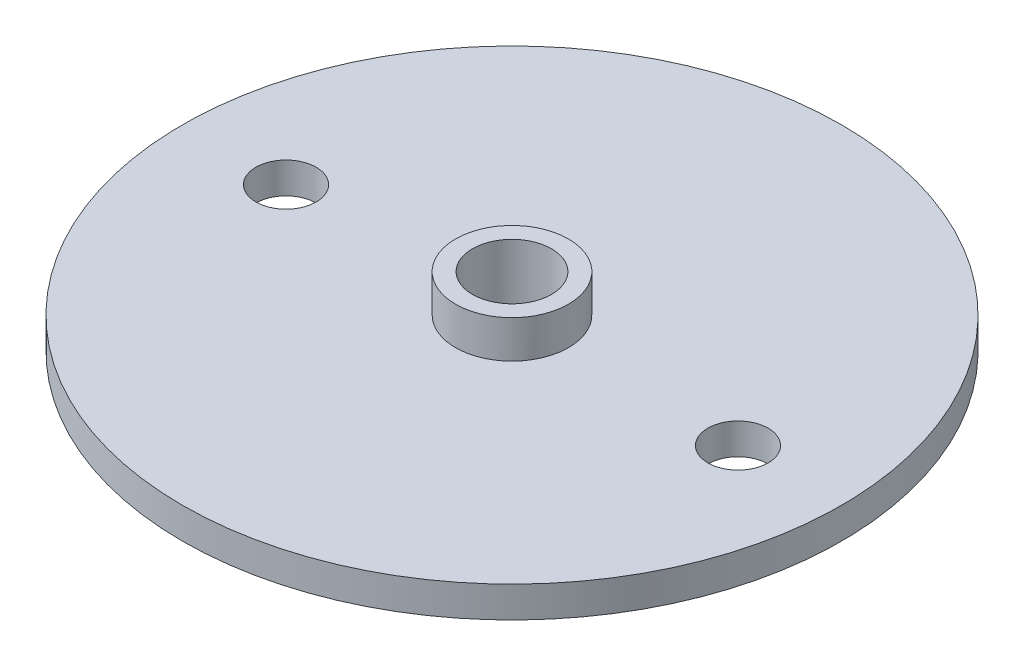
SolidWorks part; units mm, degrees
material "ABS"
ref_plane "正面" through (0, 0, 0) normal (0, 0, 1) x (1, 0, 0)
ref_plane "平面" through (0, 0, 0) normal (0, 1, 0) x (1, 0, 0)
ref_plane "右側面" through (0, 0, 0) normal (1, 0, 0) x (0, 0, -1)
sketch "ｽｹｯﾁ1" plane through (0, 0, 0) normal (0, 1, 0) x (1, 0, 0)
  circle A0 centre (0, 0) radius 2.1
  circle A1 centre (0, 0) radius 3
  dimension "D1" = 6
  dimension "D2" = 4.2
extrude "ﾎﾞｽ - 押し出し1" add sketch "ｽｹｯﾁ1" along normal blind 3
sketch "ｽｹｯﾁ2" plane through (0, 0, 0) normal (0, -1, 0) x (1, 0, 0)
  circle A0 centre (0, 0) radius 17.5
  circle A1 centre (0, 0) radius 2.1 construction
  circle A2 centre (0, 0) radius 2.1
  dimension "40" = 35
extrude "ﾎﾞｽ - 押し出し2" add sketch "ｽｹｯﾁ2" along normal blind 0.65 and the other way blind 1
sketch "ｽｹｯﾁ3" plane through (0, 1, 0) normal (0, 1, 0) x (1, 0, 0)
  line L0 (0, -1.65) -> (0, 1.65) construction
  circle A0 centre (-12, 0) radius 1.6
  circle A1 centre (12, 0) radius 1.6
  dimension "D1" = 3.2
  dimension "D2" = 12
extrude "ｶｯﾄ - 押し出し1" cut sketch "ｽｹｯﾁ3" against normal through all
